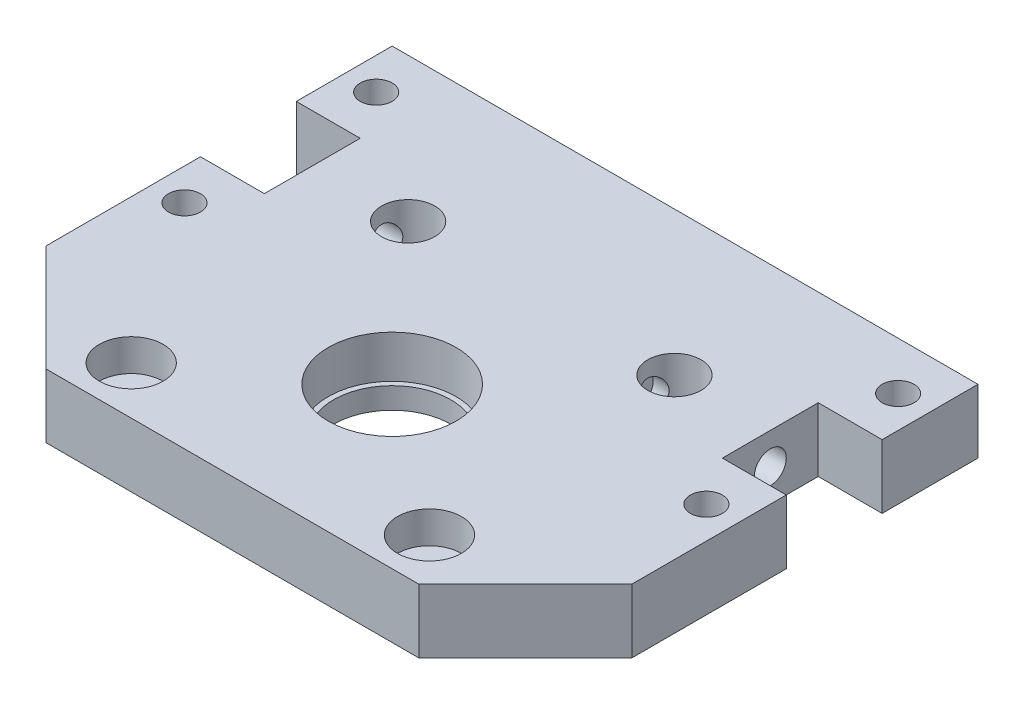
SolidWorks part; units mm, degrees
material "HDPE-green"
ref_plane "Front Plane" through (0, 0, 0) normal (0, 0, 1) x (1, 0, 0)
ref_plane "Top Plane" through (0, 0, 0) normal (0, 1, 0) x (1, 0, 0)
ref_plane "Right Plane" through (0, 0, 0) normal (1, 0, 0) x (0, 0, -1)
sketch "Sketch1" plane through (0, 0, 0) normal (0, 1, 0) x (1, 0, 0)
  line L1 (-33, 25) -> (33, 25)
  line L2 (-33, 25) -> (-33, -60)
  line L3 (-33, -60) -> (33, -60)
  line L4 (33, 25) -> (33, -60)
  circle A0 centre (0, -30) radius 11
  dimension "D6" = 22
  dimension "D1" = 66
  dimension "D2" = 33
  dimension "D3" = 25
  dimension "D4" = 60
  dimension "D5" = 30
extrude "Boss-Extrude1" add sketch "Sketch1" along normal blind 12
sketch "Sketch3" plane through (0, 12, 0) normal (0, 1, 0) x (1, 0, 0)
  line L1 (55, 7) -> (43, 7)
  line L2 (33, 25) -> (33, -60)
  line L3 (43, 7) -> (43, -11)
  line L4 (43, -11) -> (55, -11)
  line L6 (33, -60) -> (55, -60)
  line L7 (55, -60) -> (55, -11)
  line L8 (33, 25) -> (55, 25)
  line L9 (55, 7) -> (55, 25)
  dimension "D1" = 12
  dimension "D2" = 18
  dimension "D3" = 18
  dimension "D4" = 22
extrude "Boss-Extrude3" add sketch "Sketch3" against normal blind 12
mirror "Mirror1" about plane through (0, 0, 0) normal (1, 0, 0) of "Boss-Extrude3"
sketch "Sketch4" plane through (0, 12, 0) normal (0, 1, 0) x (1, 0, 0)
  circle A0 centre (0, -30) radius 12
  dimension "D1" = 24
extrude "Cut-Extrude1" cut sketch "Sketch4" against normal blind 8
sketch "Sketch6" plane through (0, 12, 0) normal (0, 1, 0) x (1, 0, 0)
  line L0 (-63.5336, -51) -> (64.8117, -51) construction
  circle A0 centre (0, -30) radius 12 construction
  circle A1 centre (-28, -51) radius 6
  circle A2 centre (28, -51) radius 6
  dimension "D2" = 28
  dimension "D3" = 28
  dimension "D4" = 12
  dimension "D5" = 12
  dimension "D1" = 21
extrude "Cut-Extrude2" cut sketch "Sketch6" against normal blind 6
chamfer "Chamfer1" distance 20 angle 45 2 edges at (55, 6, 60) (-55, 6, 60)
sketch "Sketch7" plane through (0, 12, 0) normal (0, 1, 0) x (1, 0, 0)
  line L0 (-49, 22.071) -> (-49, -31.0852) construction
  line L1 (-59.9918, 16) -> (-35.4854, 16) construction
  line L2 (-63.8876, -20) -> (-39.0752, -20) construction
  line L3 (-55, -11) -> (-43, -11) construction
  line L4 (-42.1899, -2) -> (-20.2042, -2) construction
  line L6 (-43, -11) -> (-43, 7) construction
  circle A0 centre (-49, 16) radius 3
  circle A1 centre (-49, -20) radius 3
  circle A2 centre (-25, -2) radius 5
  dimension "D2" = 6
  dimension "D3" = 6
  dimension "D4" = 18
  dimension "D5" = 10
  dimension "D1" = 9
extrude "Cut-Extrude3" cut sketch "Sketch7" against normal up to next
sketch "Sketch9" plane through (-43, 0, 0) normal (-1, 0, 0) x (0, 0, 1)
  line L0 (11, 12) -> (-7, 12) construction
  line L1 (-7, 0) -> (-7, 12) construction
  circle A0 centre (2, 6) radius 3
  dimension "D1" = 6
  dimension "D2" = 6
  dimension "D3" = 9
extrude "Cut-Extrude5" cut sketch "Sketch9" against normal blind 25
mirror "Mirror2" about plane through (0, 0, 0) normal (1, 0, 0) of "Cut-Extrude5", "Cut-Extrude3"
